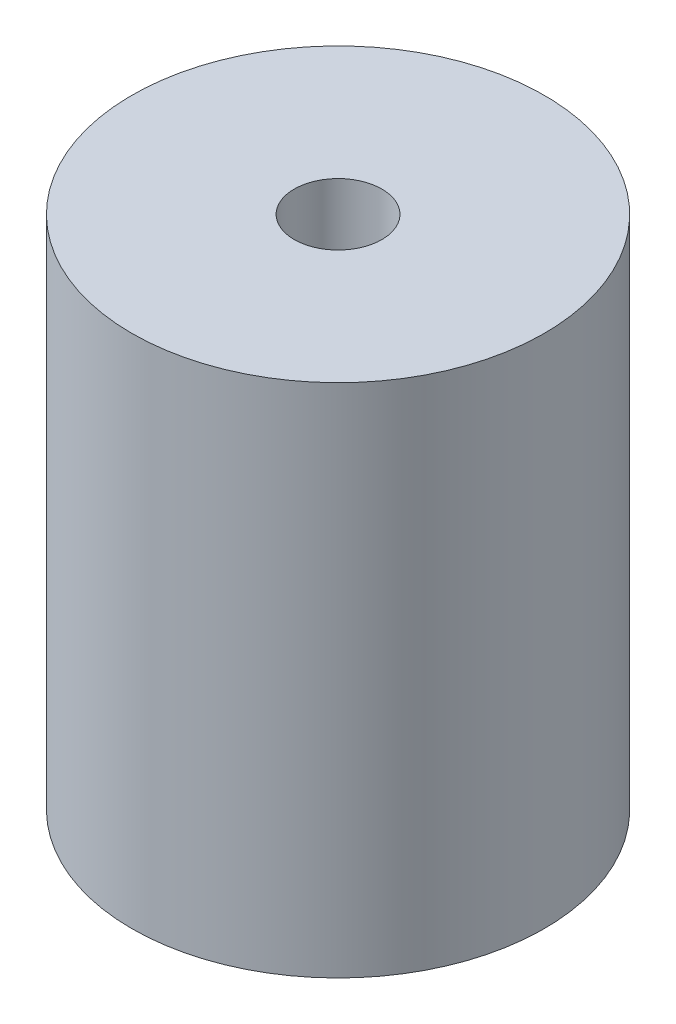
SolidWorks part; units mm, degrees
ref_plane "前视基准面" through (0, 0, 0) normal (0, 0, 1) x (1, 0, 0)
ref_plane "上视基准面" through (0, 0, 0) normal (0, 1, 0) x (1, 0, 0)
ref_plane "右视基准面" through (0, 0, 0) normal (1, 0, 0) x (0, 0, -1)
other "Configuration Table"
sketch "草图1" plane through (0, 0, 0) normal (0, 1, 0) x (1, 0, 0)
  line L1 (-5, 5) -> (5, 5) construction
  line L2 (-5, 5) -> (-5, -5) construction
  line L3 (-5, -5) -> (5, -5) construction
  line L4 (5, 5) -> (5, -5) construction
  line L5 (-5, 5) -> (5, -5) construction
  line L6 (-5, -5) -> (5, 5) construction
  circle A0 centre (0, 0) radius 1.7
  circle A1 centre (0, 0) radius 8
  dimension "D1" = 3.4
  dimension "D2" = 16
  dimension "D3" = 10
  dimension "D4" = 10
extrude "凸台-拉伸1" add sketch "草图1" along normal blind 20
